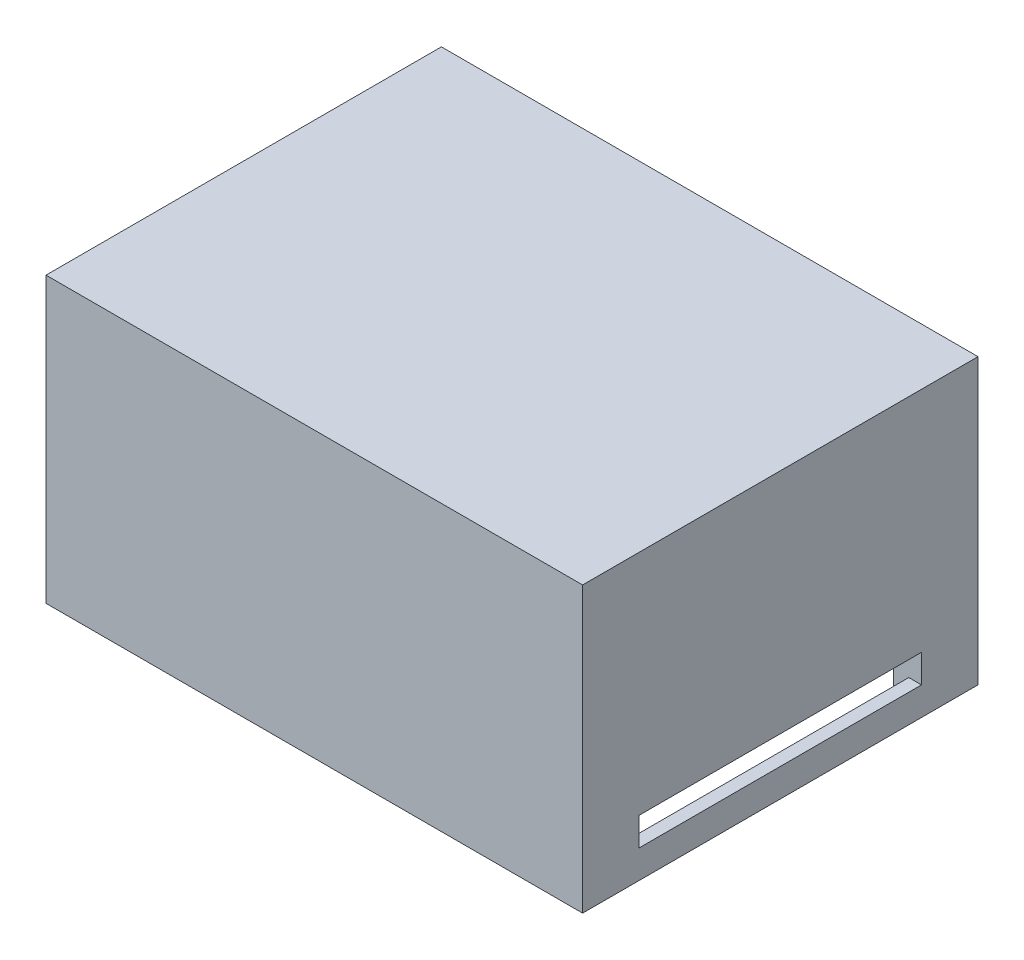
SolidWorks part; units mm, degrees
ref_plane "Front Plane" through (0, 0, 0) normal (0, 0, 1) x (1, 0, 0)
ref_plane "Top Plane" through (0, 0, 0) normal (0, 1, 0) x (1, 0, 0)
ref_plane "Right Plane" through (0, 0, 0) normal (1, 0, 0) x (0, 0, -1)
sketch "Sketch1" plane through (0, 0, 0) normal (0, 0, 1) x (1, 0, 0)
  line L1 (0, 0) -> (48.26, 0)
  line L2 (0, 0) -> (0, -25.5651)
  line L3 (0, -25.5651) -> (48.26, -25.5651)
  line L4 (48.26, 0) -> (48.26, -25.5651)
  dimension "D1" = 48.26
  dimension "D2" = 25.5651
extrude "Boss-Extrude1" add sketch "Sketch1" along normal mid plane 35.56 contours L1 L4 L3 L2
shell "Shell1" thickness 2.54
sketch "Sketch2" plane through (0, -2.54, 0) normal (0, -1, 0) x (1, 0, 0)
  circle A0 centre (10.16, 0) radius 1.5875
  point P2 (0, 0)
  dimension "D1" = 3.175
  dimension "D2" = 10.16
extrude "Boss-Extrude2" add sketch "Sketch2" along normal blind 25.4
sketch "Sketch3" plane through (0, 0, 0) normal (0, 0, 1) x (1, 0, 0)
  line L0 (2.54, -25.5651) -> (2.54, -20.4851)
  line L1 (0, -25.5651) -> (48.26, -25.5651) construction
  line L2 (2.54, -20.4851) -> (0, -20.4851)
  line L3 (0, 0) -> (0, -25.5651) construction
  line L4 (0, -20.4851) -> (0, -23.0251)
  line L5 (0.508, -25.5651) -> (1.143, -23.0251)
  line L6 (1.143, -23.0251) -> (0, -23.0251)
  line L7 (47.752, -25.5651) -> (47.117, -23.0251)
  line L8 (47.117, -23.0251) -> (48.26, -23.0251)
  line L9 (48.26, 0) -> (48.26, -25.5651) construction
  line L10 (48.26, -23.0251) -> (48.26, -20.4851)
  line L11 (48.26, -20.4851) -> (45.72, -20.4851)
  line L12 (45.72, -20.4851) -> (45.72, -25.5651)
  line L13 (45.72, -25.5651) -> (47.752, -25.5651)
  line L14 (0.508, -25.5651) -> (2.54, -25.5651)
  point P14 (0, -25.5651)
  point P21 (0, -25.5651)
  point P22 (0, 0)
  point P23 (0.459, -25.5651)
  point P24 (47.6396, -25.5651)
  dimension "D1" = 5.08
  dimension "D2" = 2.54
  dimension "D3" = 2.54
  dimension "D4" = 1.143
  dimension "D5" = 2.54
  dimension "D6" = 1.143
  dimension "D7" = 2.54
  dimension "D8" = 5.08
  dimension "D9" = 0.508
  dimension "D10" = 0.508
extrude "Cut-Extrude1" cut sketch "Sketch3" against normal mid plane 25.4
